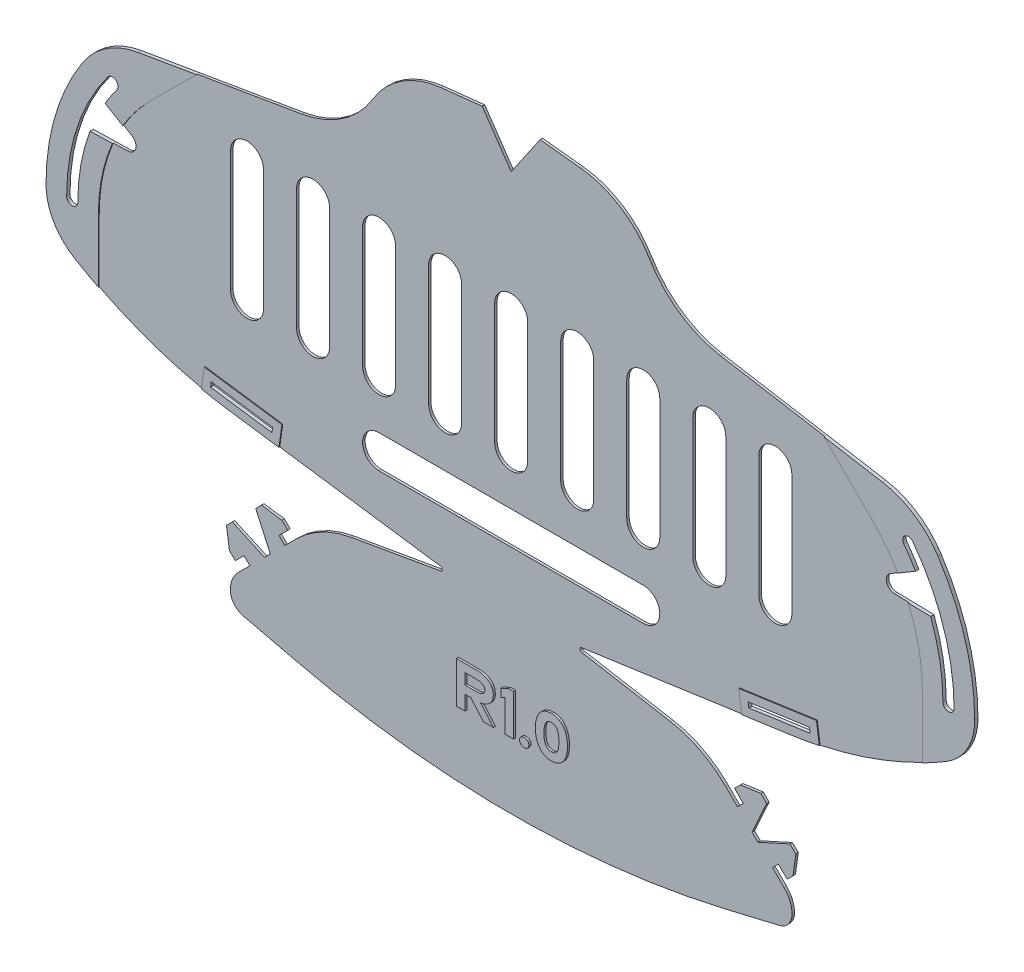
SolidWorks part; units mm, degrees
ref_plane "Front Plane" through (0, 0, 0) normal (0, 0, 1) x (1, 0, 0)
ref_plane "Top Plane" through (0, 0, 0) normal (0, 1, 0) x (1, 0, 0)
ref_plane "Right Plane" through (0, 0, 0) normal (1, 0, 0) x (0, 0, -1)
sketch "Sketch1" plane through (0, 0, 0) normal (0, 0, 1) x (1, 0, 0)
  line L0 (0, 0) -> (0, -145) construction
  line L1 (-14, -102) -> (14, -102) construction
  line L2 (-112.5, -69) -> (112.5, -69) construction
  line L3 (0, -10.2352) -> (-7, 0)
  line L4 (0, -10.2352) -> (7, 0)
  line L5 (7, 0) -> (16.9419, -1.0768)
  line L6 (-90.1804, -30.1909) -> (-50.7439, -23.5)
  line L7 (90.1804, -30.1909) -> (50.7439, -23.5)
  line L8 (-14, -102) -> (-68.2662, -94.2919)
  line L9 (-7, 0) -> (-16.9419, -1.0768)
  line L10 (14, -102) -> (68.2662, -94.2919)
  line L11 (-103.5977, -39) -> (-103.5977, -69) construction
  line L12 (-14, -102) -> (-38.6266, -106.305)
  line L13 (-52, -113.2546) -> (-54.8283, -116.0832)
  line L14 (52, -113.2546) -> (54.8283, -116.0832)
  line L15 (14, -102) -> (38.6266, -106.305)
  line L16 (-54.8283, -116.0832) -> (-56.2426, -114.669)
  line L17 (-56.2426, -114.669) -> (-54.1214, -112.5476)
  line L18 (-54.1214, -112.5476) -> (-55.5356, -111.1334)
  line L19 (-55.5356, -111.1334) -> (-60.4854, -110.4265)
  line L20 (-60.4854, -110.4265) -> (-68.9703, -118.9122)
  line L21 (-64.7275, -123.1546) -> (-63.3132, -124.5688)
  line L22 (-63.3132, -124.5688) -> (-66.1415, -127.3973)
  line L23 (-64.7275, -123.1546) -> (-66.8487, -125.2761)
  line L24 (-66.8487, -125.2761) -> (-68.263, -123.8619)
  line L25 (-68.9703, -118.9122) -> (-68.263, -123.8619)
  line L26 (68.9703, -118.9122) -> (68.263, -123.8619)
  line L27 (66.8487, -125.2761) -> (68.263, -123.8619)
  line L28 (64.7275, -123.1546) -> (66.8487, -125.2761)
  line L29 (63.3132, -124.5688) -> (66.1415, -127.3973)
  line L30 (64.7275, -123.1546) -> (63.3132, -124.5688)
  line L31 (60.4854, -110.4265) -> (68.9703, -118.9122)
  line L32 (55.5356, -111.1334) -> (60.4854, -110.4265)
  line L33 (54.1214, -112.5476) -> (55.5356, -111.1334)
  line L34 (56.2426, -114.669) -> (54.1214, -112.5476)
  line L35 (54.8283, -116.0832) -> (56.2426, -114.669)
  line L36 (-64.9691, -135.8852) -> (-52.4361, -138.8607)
  line L37 (64.9691, -135.8852) -> (52.4361, -138.8607)
  line L38 (-68.9703, -118.9122) -> (-64.7275, -123.1546) construction
  line L39 (-60.4854, -110.4265) -> (-56.2426, -114.669) construction
  arc A0 (-16.9419, -1.0768) -> (-33.4614, -11.6696) centre (-14.5729, -22.9489) ccw
  arc A1 (-33.4614, -11.6696) -> (-50.7439, -23.5) centre (-54.9257, 1.1478) cw
  arc A2 (-103.5977, -39) -> (-90.1804, -30.1909) centre (-86.8349, -49.9091) cw
  arc A3 (-112.5, -69) -> (-103.5977, -39) centre (-57.5, -69) cw
  arc A4 (112.5, -69) -> (103.5977, -39) centre (57.5, -69) ccw
  arc A5 (103.5977, -39) -> (90.1804, -30.1909) centre (86.8349, -49.9091) ccw
  arc A6 (16.9419, -1.0768) -> (33.4614, -11.6696) centre (14.5729, -22.9489) cw
  arc A7 (33.4614, -11.6696) -> (50.7439, -23.5) centre (54.9257, 1.1478) ccw
  arc A8 (-112.5, -69) -> (-105.7111, -81) centre (-98.5, -69) ccw
  arc A9 (-105.7111, -81) -> (-68.2662, -94.2919) centre (-54.2032, 4.7143) ccw
  arc A10 (112.5, -69) -> (105.7111, -81) centre (98.5, -69) cw
  arc A11 (105.7111, -81) -> (68.2662, -94.2919) centre (54.2032, 4.7143) cw
  arc A12 (-38.6266, -106.305) -> (-52, -113.2546) centre (-34.3216, -130.9315) ccw
  arc A13 (38.6266, -106.305) -> (52, -113.2546) centre (34.3216, -130.9315) cw
  arc A14 (-66.1415, -127.3973) -> (-68.0451, -131.9933) centre (-61.5451, -131.9933) ccw
  arc A15 (-68.0451, -131.9933) -> (-64.9691, -135.8852) centre (-64.0451, -131.9933) ccw
  arc A16 (68.0451, -131.9933) -> (64.9691, -135.8852) centre (64.0451, -131.9933) cw
  arc A17 (66.1415, -127.3973) -> (68.0451, -131.9933) centre (61.5451, -131.9933) cw
  arc A19 (-52.4361, -138.8607) -> (0, -145) centre (0, 82) ccw
  arc A20 (52.4361, -138.8607) -> (0, -145) centre (0, 82) cw
  point P8 (0, -102)
  point P11 (0, -69)
  dimension "D5" = 55
  dimension "D11" = 20
  dimension "D13" = 25
  dimension "D16" = 14
  dimension "D15" = 22
  dimension "D18" = 100
  dimension "D22" = 25
  dimension "D31" = 6.5
  dimension "D32" = 4
  dimension "D34" = 227
  dimension "D1" = 145
  dimension "D2" = 28
  dimension "D3" = 43
  dimension "D4" = 76
  dimension "D6" = 225
  dimension "D7" = 14
  dimension "D8" = 12.4
  dimension "D9" = 10
  dimension "D10" = 30
  dimension "D12" = 40
  dimension "D14" = 45.5
  dimension "D17" = 12
  dimension "D19" = 18
  dimension "D20" = 25
  dimension "D21" = 4
  dimension "D23" = 38
  dimension "D24" = 2
  dimension "D25" = 3
  dimension "D26" = 2
  dimension "D27" = 18
  dimension "D29" = 8
  dimension "D30" = 4
extrude "Main Shape" add sketch "Sketch1" along normal blind 0.6
sketch "Sketch2" plane through (0, 0, 0.6) normal (0, 0, 1) x (1, 0, 0)
  line L0 (0, -0.33) -> (0, 0.33) construction
  arc A0 (-96.42, -39.81) -> (-106.15, -69) centre (-57.5, -69) ccw construction
  arc A1 (-97.5, -39) -> (-107.5, -69) centre (-57.5, -69) ccw
  arc A2 (-95.34, -40.62) -> (-104.8, -69) centre (-57.5, -69) ccw
  arc A3 (-95.34, -40.62) -> (-97.5, -39) centre (-96.42, -39.81) ccw
  arc A4 (-107.5, -69) -> (-104.8, -69) centre (-106.15, -69) ccw
  arc A6 (-103.5977, -39) -> (-112.5, -69) centre (-57.5, -69) ccw construction
  arc A7 (96.42, -39.81) -> (106.15, -69) centre (57.5, -69) cw construction
  arc A8 (97.5, -39) -> (107.5, -69) centre (57.5, -69) cw
  arc A9 (95.34, -40.62) -> (104.8, -69) centre (57.5, -69) cw
  arc A10 (95.34, -40.62) -> (97.5, -39) centre (96.42, -39.81) cw
  arc A11 (107.5, -69) -> (104.8, -69) centre (106.15, -69) cw
  point P3 (-103.6534, -53.6155)
  point P19 (103.6534, -53.6155)
  dimension "D1" = 5
  dimension "D2" = 1.35
extrude "Elastic Attachment Points" cut sketch "Sketch2" against normal through all
sketch "Sketch7" plane through (0, 0, 0.6) normal (0, 0, 1) x (1, 0, 0)
  line L0 (-99.8, -69) -> (-99.8, -84.2853)
  line L1 (-87.321, -39) -> (-76.0466, -27.7929)
  line L2 (-50.7439, -23.5) -> (-90.1804, -30.1909) construction
  line L3 (-76.0466, -27.7929) -> (-90.1804, -30.1909)
  line L4 (0, -0.33) -> (0, 0.33) construction
  line L5 (76.0466, -27.7929) -> (90.1804, -30.1909)
  line L6 (87.321, -39) -> (76.0466, -27.7929)
  line L7 (99.8, -69) -> (99.8, -84.2853)
  arc A0 (-99.8, -69) -> (-87.321, -39) centre (-57.5, -69) cw
  arc A1 (-95.34, -40.62) -> (-104.8, -69) centre (-57.5, -69) ccw construction
  arc A2 (-105.7111, -81) -> (-68.2662, -94.2919) centre (-54.2032, 4.7143) ccw construction
  arc A3 (-112.5, -69) -> (-105.7111, -81) centre (-98.5, -69) ccw construction
  arc A4 (-103.5977, -39) -> (-112.5, -69) centre (-57.5, -69) ccw construction
  arc A5 (-90.1804, -30.1909) -> (-103.5977, -39) centre (-86.8349, -49.9091) ccw construction
  arc A6 (-105.7111, -81) -> (-99.8, -84.2853) centre (-54.2032, 4.7143) ccw
  arc A7 (-112.5, -69) -> (-105.7111, -81) centre (-98.5, -69) ccw
  arc A8 (-103.5977, -39) -> (-112.5, -69) centre (-57.5, -69) ccw
  arc A9 (-90.1804, -30.1909) -> (-103.5977, -39) centre (-86.8349, -49.9091) ccw
  arc A10 (90.1804, -30.1909) -> (103.5977, -39) centre (86.8349, -49.9091) cw
  arc A11 (103.5977, -39) -> (112.5, -69) centre (57.5, -69) cw
  arc A12 (112.5, -69) -> (105.7111, -81) centre (98.5, -69) cw
  arc A13 (105.7111, -81) -> (99.8, -84.2853) centre (54.2032, 4.7143) cw
  arc A14 (99.8, -69) -> (87.321, -39) centre (57.5, -69) ccw
  arc A15 (-107.5, -69) -> (-104.8, -69) centre (-106.15, -69) ccw construction
  arc A16 (-95.34, -40.62) -> (-97.5, -39) centre (-96.42, -39.81) ccw construction
  arc A17 (-97.5, -39) -> (-107.5, -69) centre (-57.5, -69) ccw construction
  arc A18 (-107.5, -69) -> (-104.8, -69) centre (-106.15, -69) ccw
  arc A19 (-95.34, -40.62) -> (-97.5, -39) centre (-96.42, -39.81) ccw
  arc A20 (-95.34, -40.62) -> (-104.8, -69) centre (-57.5, -69) ccw
  arc A21 (-97.5, -39) -> (-107.5, -69) centre (-57.5, -69) ccw
  arc A22 (104.8, -69) -> (107.5, -69) centre (106.15, -69) ccw construction
  arc A23 (97.5, -39) -> (95.34, -40.62) centre (96.42, -39.81) ccw construction
  arc A24 (104.8, -69) -> (95.34, -40.62) centre (57.5, -69) ccw construction
  arc A25 (107.5, -69) -> (97.5, -39) centre (57.5, -69) ccw construction
  arc A26 (104.8, -69) -> (107.5, -69) centre (106.15, -69) ccw
  arc A27 (97.5, -39) -> (95.34, -40.62) centre (96.42, -39.81) ccw
  arc A28 (104.8, -69) -> (95.34, -40.62) centre (57.5, -69) ccw
  arc A29 (107.5, -69) -> (97.5, -39) centre (57.5, -69) ccw
  dimension "D1" = 5
extrude "Reinforced Attachment Points" add sketch "Sketch7" along normal blind 0.2
sketch "Sketch6" plane through (0, 0, 0.6) normal (0, 0, 1) x (1, 0, 0)
  line L0 (-72.6274, -91.6524) -> (-57.7765, -93.7618)
  line L1 (-57.7765, -93.7618) -> (-57.6078, -92.5738)
  line L2 (-57.6078, -92.5738) -> (-72.4587, -90.4643)
  line L3 (-72.4587, -90.4643) -> (-72.6274, -91.6524)
  line L4 (-68.2662, -94.2919) -> (-14, -102) construction
  line L5 (-65.0332, -91.519) -> (-65.202, -92.7071) construction
  line L13 (0, -0.33) -> (0, 0.33) construction
  line L14 (65.0332, -91.519) -> (65.202, -92.7071) construction
  line L15 (72.6274, -91.6524) -> (72.4587, -90.4643)
  line L16 (57.6078, -92.5738) -> (57.7765, -93.7618)
  line L22 (57.6078, -92.5738) -> (72.4587, -90.4643)
  line L24 (72.6274, -91.6524) -> (57.7765, -93.7618)
  dimension "D1" = 2
  dimension "D2" = 15
  dimension "D3" = 52
  dimension "D4" = 1.2
extrude "Tab Slits" cut sketch "Sketch6" against normal through all
sketch "Sketch9" plane through (0, 0, 0.6) normal (0, 0, 1) x (1, 0, 0)
  line L4 (-57.7765, -93.7618) -> (-57.6078, -92.5738) construction
  line L5 (-72.6274, -91.6524) -> (-57.7765, -93.7618) construction
  line L6 (-72.4587, -90.4643) -> (-72.6274, -91.6524) construction
  line L7 (-57.6078, -92.5738) -> (-72.4587, -90.4643) construction
  line L12 (-57.7765, -93.7618) -> (-57.6078, -92.5738)
  line L13 (-72.6274, -91.6524) -> (-57.7765, -93.7618)
  line L14 (-72.4587, -90.4643) -> (-72.6274, -91.6524)
  line L15 (-57.6078, -92.5738) -> (-72.4587, -90.4643)
  line L16 (-56.0776, -96.0232) -> (-55.3464, -90.8749)
  line L17 (-68.2662, -94.2919) -> (-14, -102) construction
  line L18 (-55.3464, -90.8749) -> (-74.1575, -88.2029)
  line L19 (-74.1575, -88.2029) -> (-74.8573, -93.1295)
  line L20 (-68.2662, -94.2919) -> (-56.0776, -96.0232)
  line L21 (0, -0.33) -> (0, 0.33) construction
  line L22 (68.2662, -94.2919) -> (56.0776, -96.0232)
  line L23 (74.1575, -88.2029) -> (74.8573, -93.1295)
  line L24 (55.3464, -90.8749) -> (74.1575, -88.2029)
  line L25 (56.0776, -96.0232) -> (55.3464, -90.8749)
  line L26 (57.6078, -92.5738) -> (72.4587, -90.4643)
  line L27 (72.4587, -90.4643) -> (72.6274, -91.6524)
  line L28 (72.6274, -91.6524) -> (57.7765, -93.7618)
  line L29 (57.7765, -93.7618) -> (57.6078, -92.5738)
  arc A0 (-99.8, -84.2853) -> (-68.2662, -94.2919) centre (-54.2032, 4.7143) ccw construction
  arc A1 (-74.8573, -93.1295) -> (-68.2662, -94.2919) centre (-54.2032, 4.7143) ccw
  arc A2 (74.8573, -93.1295) -> (68.2662, -94.2919) centre (54.2032, 4.7143) cw
  dimension "D1" = 2
  dimension "D2" = 2
  dimension "D3" = 2
extrude "Reinforced Tab Slits" add sketch "Sketch9" along normal blind 0.2
sketch "Sketch11" plane through (0, 0, 0.6) normal (0, 0, 1) x (1, 0, 0)
  line L0 (-67.5562, -117.4979) -> (-59.7778, -121.0331)
  line L1 (-60.4854, -110.4265) -> (-68.9703, -118.9122) construction
  line L2 (-59.7778, -121.0331) -> (-58.3637, -119.6188)
  line L3 (-58.3637, -119.6188) -> (-61.8996, -111.8408)
  line L4 (-61.8996, -111.8408) -> (-67.5562, -117.4979)
  line L6 (-58.3637, -119.6188) -> (-54.8283, -116.0832) construction
  line L7 (-59.7778, -121.0331) -> (-63.3132, -124.5688) construction
  line L10 (0, -0.33) -> (0, 0.33) construction
  line L11 (59.7778, -121.0331) -> (63.3132, -124.5688) construction
  line L12 (58.3637, -119.6188) -> (54.8283, -116.0832) construction
  line L13 (61.8996, -111.8408) -> (67.5562, -117.4979)
  line L14 (58.3637, -119.6188) -> (61.8996, -111.8408)
  line L15 (59.7778, -121.0331) -> (58.3637, -119.6188)
  line L16 (67.5562, -117.4979) -> (59.7778, -121.0331)
  dimension "D1" = 2
  dimension "D2" = 2
  dimension "D3" = 5
extrude "Tab Flex Relief" cut sketch "Sketch11" against normal through all both and the other way through all
sketch "Sketch3" plane through (0, 0, 0.6) normal (0, 0, 1) x (1, 0, 0)
  line L3 (0, -10.2352) -> (0, -145) construction
  line L4 (-106.15, -69) -> (-96.42, -69) construction
  line L5 (-96.42, -69) -> (-96.42, -39.81) construction
  line L427 (0, -39.81) -> (0, -69) construction
  line L428 (4, -39.81) -> (4, -69)
  line L429 (-4, -39.81) -> (-4, -69)
  line L444 (-16, -39.81) -> (-16, -69) construction
  line L447 (-12, -39.81) -> (-12, -69)
  line L450 (-20, -39.81) -> (-20, -69)
  line L451 (-32, -39.81) -> (-32, -69) construction
  line L455 (-28, -39.81) -> (-28, -69)
  line L456 (-36, -39.81) -> (-36, -69)
  line L836 (-32, -85) -> (32, -85) construction
  line L837 (-32, -81) -> (32, -81)
  line L838 (-32, -89) -> (32, -89)
  line L839 (-64, -73) -> (64, -73) construction
  line L933 (-48, -39.81) -> (-48, -69) construction
  line L934 (-44, -39.81) -> (-44, -69)
  line L935 (-52, -39.81) -> (-52, -69)
  line L936 (-64, -39.81) -> (-64, -69) construction
  line L937 (-60, -39.81) -> (-60, -69)
  line L938 (-68, -39.81) -> (-68, -69)
  line L939 (16, -39.81) -> (16, -69) construction
  line L940 (12, -39.81) -> (12, -69)
  line L941 (20, -39.81) -> (20, -69)
  line L942 (32, -39.81) -> (32, -69) construction
  line L943 (28, -39.81) -> (28, -69)
  line L944 (36, -39.81) -> (36, -69)
  line L945 (48, -39.81) -> (48, -69) construction
  line L946 (44, -39.81) -> (44, -69)
  line L947 (52, -39.81) -> (52, -69)
  line L948 (64, -39.81) -> (64, -69) construction
  line L949 (60, -39.81) -> (60, -69)
  line L950 (68, -39.81) -> (68, -69)
  arc A2 (-52.4361, -138.8607) -> (52.4361, -138.8607) centre (0, 82) ccw construction
  arc A21 (4, -39.81) -> (-4, -39.81) centre (0, -39.81) ccw
  arc A22 (-4, -69) -> (4, -69) centre (0, -69) ccw
  arc A23 (-12, -39.81) -> (-20, -39.81) centre (-16, -39.81) ccw
  arc A24 (-20, -69) -> (-12, -69) centre (-16, -69) ccw
  arc A25 (-28, -39.81) -> (-36, -39.81) centre (-32, -39.81) ccw
  arc A26 (-36, -69) -> (-28, -69) centre (-32, -69) ccw
  arc A27 (-44, -39.81) -> (-52, -39.81) centre (-48, -39.81) ccw
  arc A28 (-52, -69) -> (-44, -69) centre (-48, -69) ccw
  arc A29 (-60, -39.81) -> (-68, -39.81) centre (-64, -39.81) ccw
  arc A30 (-68, -69) -> (-60, -69) centre (-64, -69) ccw
  arc A31 (12, -39.81) -> (20, -39.81) centre (16, -39.81) cw
  arc A32 (20, -69) -> (12, -69) centre (16, -69) cw
  arc A33 (28, -39.81) -> (36, -39.81) centre (32, -39.81) cw
  arc A34 (36, -69) -> (28, -69) centre (32, -69) cw
  arc A35 (44, -39.81) -> (52, -39.81) centre (48, -39.81) cw
  arc A36 (52, -69) -> (44, -69) centre (48, -69) cw
  arc A37 (60, -39.81) -> (68, -39.81) centre (64, -39.81) cw
  arc A38 (68, -69) -> (60, -69) centre (64, -69) cw
  arc A39 (-32, -81) -> (-32, -89) centre (-32, -85) ccw
  arc A40 (32, -89) -> (32, -81) centre (32, -85) ccw
  point P3 (-16, -54.405)
  point P18 (-32, -54.405)
  point P30 (-48, -54.405)
  point P37 (-64, -54.405)
  point P43 (16, -54.405)
  point P50 (32, -54.405)
  point P57 (48, -54.405)
  point P64 (64, -54.405)
  point P71 (0, -85)
  point P414 (0, -54.405)
  dimension "D5" = 8
  dimension "D1" = 8
  dimension "D2" = 5
  dimension "D3" = 8
  dimension "D4" = 8
extrude "Breathing Slits" cut sketch "Sketch3" against normal through all
sketch "Sketch8" plane through (0, 0, 0.6) normal (0, 0, 1) x (1, 0, 0)
  line L0 (-67.0266, -128.5) -> (67.0266, -128.5) construction
  line L1 (0, -10.2352) -> (0, -145) construction
  arc A0 (-52.4361, -138.8607) -> (52.4361, -138.8607) centre (0, 82) ccw construction
  arc A1 (-66.1415, -127.3973) -> (-68.0451, -131.9933) centre (-61.5451, -131.9933) ccw construction
  text T0 "<b>R1.0</b>" font "Double Porter 3" height 10
  point P9 (0, -128.5)
  dimension "D2" = 16.5
extrude "Version Number" add sketch "Sketch8" along normal blind 0.5
fillet "Fillet1" radius 0.5 2 edges at (-14, -102, 0.3) (14, -102, 0.3)
sketch "Sketch12" plane through (0, 0, 0.8) normal (0, 0, 1) x (1, 0, 0)
  line L0 (-98.1829, -44.8713) -> (-91.8731, -48.6136)
  line L1 (-98.1829, -44.8713) -> (-89.3972, -30.058) construction
  line L2 (-76.0466, -27.7929) -> (-90.1804, -30.1909) construction
  line L3 (-101.8445, -52.5422) -> (-92.8469, -52.3333)
  line L4 (0, -0.44) -> (0, 0.44) construction
  line L5 (98.1829, -44.8713) -> (89.3972, -30.058) construction
  line L6 (101.8445, -52.5422) -> (92.8469, -52.3333)
  line L7 (98.1829, -44.8713) -> (91.8731, -48.6136)
  arc A0 (-95.34, -40.62) -> (-104.8, -69) centre (-57.5, -69) ccw construction
  arc A1 (-92.8469, -52.3333) -> (-91.8731, -48.6136) centre (-92.8933, -50.3338) ccw
  arc A2 (-98.1829, -44.8713) -> (-101.8445, -52.5422) centre (-57.5, -69) ccw
  arc A3 (98.1829, -44.8713) -> (101.8445, -52.5422) centre (57.5, -69) cw
  arc A4 (92.8469, -52.3333) -> (91.8731, -48.6136) centre (92.8933, -50.3338) cw
  dimension "D4" = 2
  dimension "D1" = 24.1287
  dimension "D2" = 8.5
  dimension "D3" = 9
extrude "Cut-Extrude1" cut sketch "Sketch12" against normal through all both and the other way through all
